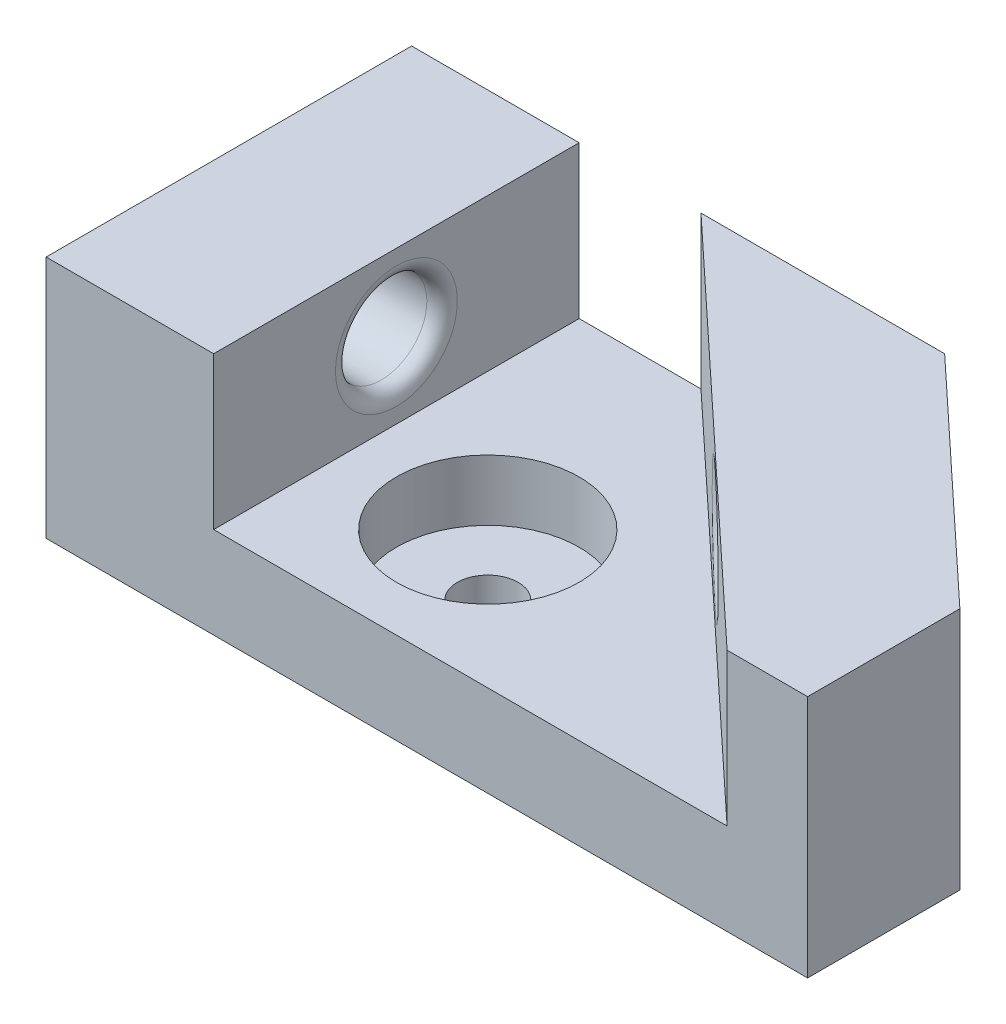
SolidWorks part; units mm, degrees
ref_plane "Front Plane" through (0, 0, 0) normal (0, 0, 1) x (1, 0, 0)
ref_plane "Top Plane" through (0, 0, 0) normal (0, 1, 0) x (1, 0, 0)
ref_plane "Right Plane" through (0, 0, 0) normal (1, 0, 0) x (0, 0, -1)
sketch "Sketch1" plane through (0, 0, 0) normal (0, 1, 0) x (1, 0, 0)
  line L1 (-3372.8754, 385.6771) -> (2977.1246, 385.6771)
  line L2 (-3372.8754, 385.6771) -> (-3372.8754, -2662.3229)
  line L3 (-3372.8754, -2662.3229) -> (2977.1246, -2662.3229)
  line L4 (2977.1246, 385.6771) -> (2977.1246, -2662.3229)
  dimension "D1" = 6350
  dimension "D2" = 3048
  dimension "D3" = 3372.8754
  dimension "D4" = 2662.3229
extrude "Boss-Extrude1" add sketch "Sketch1" along normal blind 2032
sketch "Sketch2" plane through (0, 2032, 0) normal (0, 1, 0) x (1, 0, 0)
  line L0 (1072.1246, 385.6771) -> (2977.1246, -1392.3229)
  line L1 (2977.1246, 385.6771) -> (-3372.8754, 385.6771) construction
  line L2 (2977.1246, -2662.3229) -> (2977.1246, 385.6771) construction
  line L3 (2977.1246, -1392.3229) -> (2977.1246, 385.6771)
  line L4 (2977.1246, 385.6771) -> (1072.1246, 385.6771)
  dimension "D1" = 4445
  dimension "D2" = 1270
extrude "Cut-Extrude1" cut sketch "Sketch2" against normal through all
sketch "Sketch3" plane through (0, 2032, 0) normal (0, 1, 0) x (1, 0, 0)
  line L0 (-1975.8754, 385.6771) -> (-1975.8754, -2662.3229)
  line L1 (1072.1246, 385.6771) -> (-3372.8754, 385.6771) construction
  line L2 (-3372.8754, -2662.3229) -> (2977.1246, -2662.3229) construction
  line L3 (-1975.8754, -2662.3229) -> (2305.8389, -2662.3229)
  line L4 (2305.8389, -2662.3229) -> (-959.8754, 385.6771)
  line L5 (-959.8754, 385.6771) -> (-1975.8754, 385.6771)
  line L6 (1072.1246, 385.6771) -> (2977.1246, -1392.3229) construction
  dimension "D1" = 2032
  dimension "D2" = 1016
extrude "Cut-Extrude2" cut sketch "Sketch3" against normal blind 1270
sketch "Sketch4" plane through (0, 762, 0) normal (0, 1, 0) x (1, 0, 0)
  line L0 (-1975.8754, 385.6771) -> (-1975.8754, -2662.3229) construction
  line L1 (-1975.8754, -2662.3229) -> (2305.8389, -2662.3229) construction
  circle A0 centre (-832.8754, -1519.3229) radius 762
  dimension "D1" = 1524
  dimension "D2" = 1143
  dimension "D3" = 1143
extrude "Cut-Extrude3" cut sketch "Sketch4" against normal blind 508
sketch "Sketch5" plane through (0, 254, 0) normal (0, 1, 0) x (1, 0, 0)
  line L0 (-1975.8754, -2662.3229) -> (2305.8389, -2662.3229) construction
  line L1 (-1975.8754, 385.6771) -> (-1975.8754, -2662.3229) construction
  circle A0 centre (-832.8754, -1519.3229) radius 254
  dimension "D3" = 508
  dimension "D1" = 1143
  dimension "D2" = 1143
extrude "Cut-Extrude4" cut sketch "Sketch5" against normal through all
sketch "Sketch6" plane through (-1975.8754, 0, 0) normal (1, 0, 0) x (0, 0, -1)
  line L0 (385.6771, 2032) -> (-2662.3229, 2032) construction
  line L1 (-2662.3229, 762) -> (-2662.3229, 2032) construction
  circle A0 centre (-1138.3229, 1397) radius 381
  dimension "D1" = 762
  dimension "D2" = 635
  dimension "D3" = 1524
extrude "Cut-Extrude5" cut sketch "Sketch6" against normal through all
fillet "Fillet1" radius 127 2 edges at (-1975.8754, 1397, 757.3229) (-3372.8754, 1397, 757.3229)
sketch "Sketch7" plane through (-254.4974, 0, 272.6757) normal (-0.6823, 0, 0.7311) x (0.7311, 0, 0.6823)
  line L0 (3502.2472, 762) -> (3502.2472, 2032) construction
  line L1 (3502.2472, 2032) -> (-964.8764, 2032) construction
  circle A0 centre (1470.2472, 1397) radius 381
  dimension "D1" = 762
  dimension "D2" = 2032
  dimension "D3" = 635
extrude "Cut-Extrude6" cut sketch "Sketch7" against normal through all
fillet "Fillet2" radius 127 2 edges at (2044.8809, 1397, 522.2288) (1098.8667, 1397, 1535.8155)
